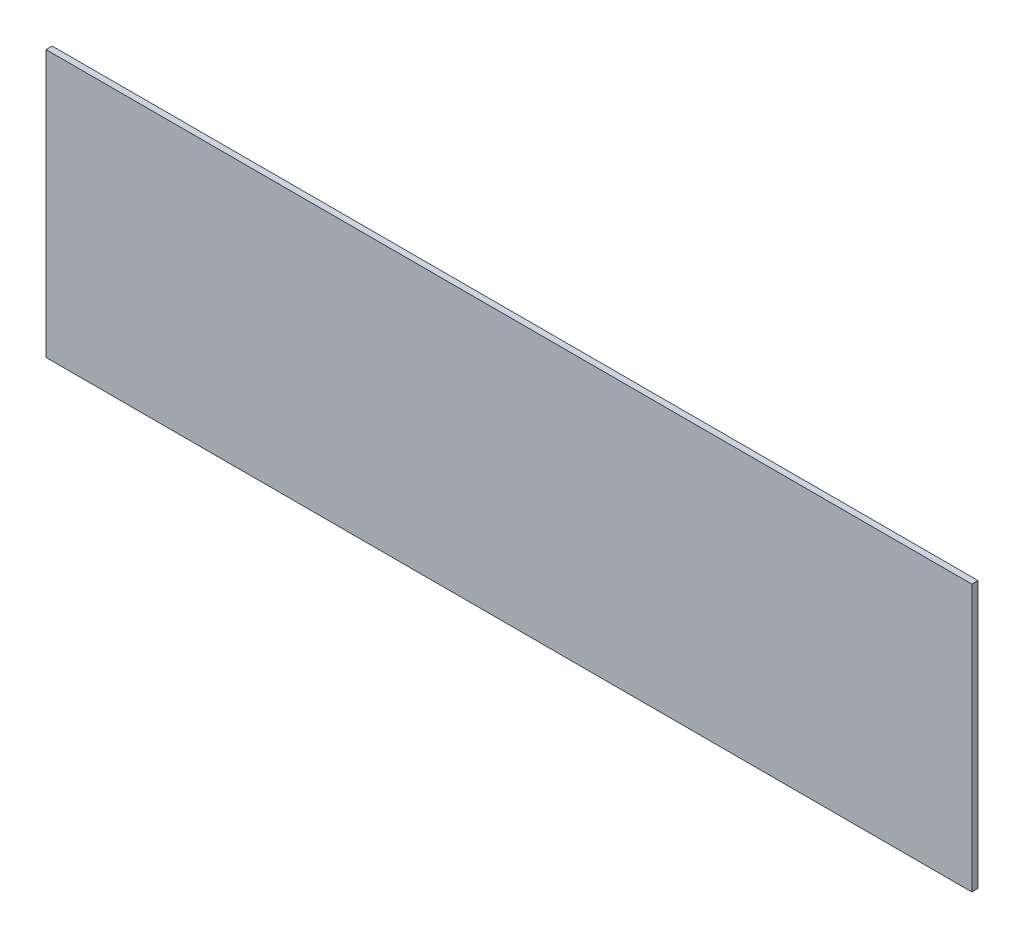
SolidWorks part; units mm, degrees
ref_plane "Front Plane" through (0, 0, 0) normal (0, 0, 1) x (1, 0, 0)
ref_plane "Top Plane" through (0, 0, 0) normal (0, 1, 0) x (1, 0, 0)
ref_plane "Right Plane" through (0, 0, 0) normal (1, 0, 0) x (0, 0, -1)
sketch "Sketch1" plane through (0, 0, 0) normal (0, 0, 1) x (1, 0, 0)
  line L1 (750, -216) -> (-750, -216)
  line L2 (750, -216) -> (750, 216)
  line L3 (750, 216) -> (-750, 216)
  line L4 (-750, -216) -> (-750, 216)
  line L5 (750, -216) -> (-750, 216) construction
  line L6 (750, 216) -> (-750, -216) construction
  point P0 (0, 0)
extrude "Boss-Extrude1" add sketch "Sketch1" along normal blind 10
